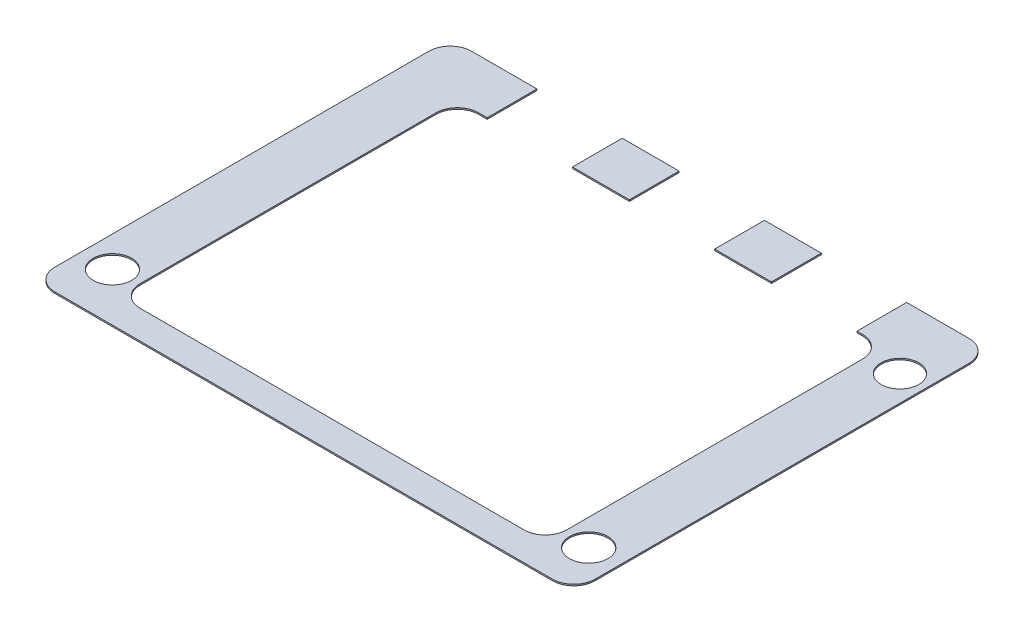
SolidWorks part; units mm, degrees
ref_plane "Front Plane" through (0, 0, 0) normal (0, 0, 1) x (1, 0, 0)
ref_plane "Top Plane" through (0, 0, 0) normal (0, 1, 0) x (1, 0, 0)
ref_plane "Right Plane" through (0, 0, 0) normal (1, 0, 0) x (0, 0, -1)
sketch "Sketch1" plane through (0, 0, 0) normal (0, 1, 0) x (1, 0, 0)
  line L0 (0, 0) -> (8, 0) construction
  line L1 (3, 0) -> (73, 0)
  line L2 (0, 3) -> (0, 52.62)
  line L4 (76, 3) -> (76, 52.62)
  line L5 (8, 0) -> (8, 4) construction
  line L6 (38, 0) -> (38, 55.62) construction
  line L7 (0, 27.81) -> (76, 27.81) construction
  line L8 (68, 0) -> (68, 4) construction
  line L9 (68, 55.62) -> (68, 51.62) construction
  line L10 (68, 55.62) -> (76, 55.62) construction
  line L11 (0, 52.62) -> (0, 55.62)
  line L12 (11, 4) -> (65, 4)
  line L13 (8, 7) -> (8, 48.62)
  line L14 (11, 51.62) -> (65, 51.62)
  line L15 (68, 7) -> (68, 48.62)
  line L16 (3, 58.62) -> (73, 58.62)
  line L17 (76, 55.62) -> (76, 52.62)
  arc A0 (8, 7) -> (11, 4) centre (11, 7) ccw
  arc A1 (65, 4) -> (68, 7) centre (65, 7) ccw
  arc A2 (68, 48.62) -> (65, 51.62) centre (65, 48.62) ccw
  arc A3 (11, 51.62) -> (8, 48.62) centre (11, 48.62) ccw
  arc A4 (0, 3) -> (3, 0) centre (3, 3) ccw
  arc A5 (73, 0) -> (76, 3) centre (73, 3) ccw
  arc A8 (0, 55.62) -> (3, 58.62) centre (3, 55.62) cw
  arc A9 (73, 58.62) -> (76, 55.62) centre (73, 55.62) cw
  point P32 (76, 0)
  point P38 (0, 55.62)
  dimension "D5" = 3
  dimension "D6" = 3
  dimension "D1" = 55.62
  dimension "D2" = 76
  dimension "D3" = 4
  dimension "D4" = 8
extrude "Boss-Extrude1" add sketch "Sketch1" along normal blind 0.2
sketch "Sketch4" plane through (0, 0, -58.62) normal (0, 0, -1) x (-1, 0, 0)
  line L0 (-73, 0.2) -> (-3, 0.2) construction
  line L1 (-64.2, 0.2) -> (-52.1922, 0.2)
  line L2 (-64.2, 0.2) -> (-64.2, 0)
  line L3 (-64.2, 0) -> (-52.1922, 0)
  line L4 (-52.1922, 0.2) -> (-52.1922, 0)
  line L5 (-73, 0) -> (-3, 0) construction
  line L7 (-44.2, 0.2) -> (-32.1984, 0.2)
  line L8 (-44.2, 0.2) -> (-44.2, 0)
  line L9 (-44.2, 0) -> (-32.1984, 0)
  line L10 (-32.1984, 0.2) -> (-32.1984, 0)
  line L11 (-24.2, 0.2) -> (-12.2, 0.2)
  line L12 (-24.2, 0.2) -> (-24.2, 0)
  line L13 (-24.2, 0) -> (-12.2, 0)
  line L14 (-12.2, 0.2) -> (-12.2, 0)
  arc A0 (-52.2, 0.2) -> (-64.2, 0.2) centre (-58.2, 0.2) ccw construction
  arc A1 (-32.2, 0.2) -> (-44.2, 0.2) centre (-38.2, 0.2) ccw construction
  arc A2 (-12.2, 0.2) -> (-24.2, 0.2) centre (-18.2, 0.2) ccw construction
extrude "Cut-Extrude3" cut sketch "Sketch4" against normal up to surface (7 mm away) up to face at (38, 0.1, -51.62)
sketch "Sketch5" plane through (0, 0, 0) normal (0, -1, 0) x (-1, 0, 0)
  circle A0 centre (-72.4023, 49.4773) radius 2.65
  dimension "D1" = 5.3
extrude "Cut-Extrude4" cut sketch "Sketch5" against normal through all
sketch "Sketch6" plane through (0, 0, 0) normal (0, -1, 0) x (-1, 0, 0)
  line L0 (-3, 0) -> (-73, 0) construction
  line L1 (0, 55.62) -> (0, 3) construction
  circle A0 centre (-4.3106, 6.8021) radius 2.7
  dimension "D1" = 5.4
  dimension "D2" = 90
  dimension "D3" = 4.3106
extrude "Cut-Extrude5" cut sketch "Sketch6" against normal through all
sketch "Sketch7" plane through (0, 0, 0) normal (0, -1, 0) x (-1, 0, 0)
  line L0 (-76, 3) -> (-76, 55.62) construction
  line L1 (-3, 0) -> (-73, 0) construction
  circle A0 centre (-71.7, 6.4) radius 2.7
  dimension "D1" = 5.4
  dimension "D2" = 4.3
  dimension "D3" = 6.4
extrude "Cut-Extrude6" cut sketch "Sketch7" against normal through all
